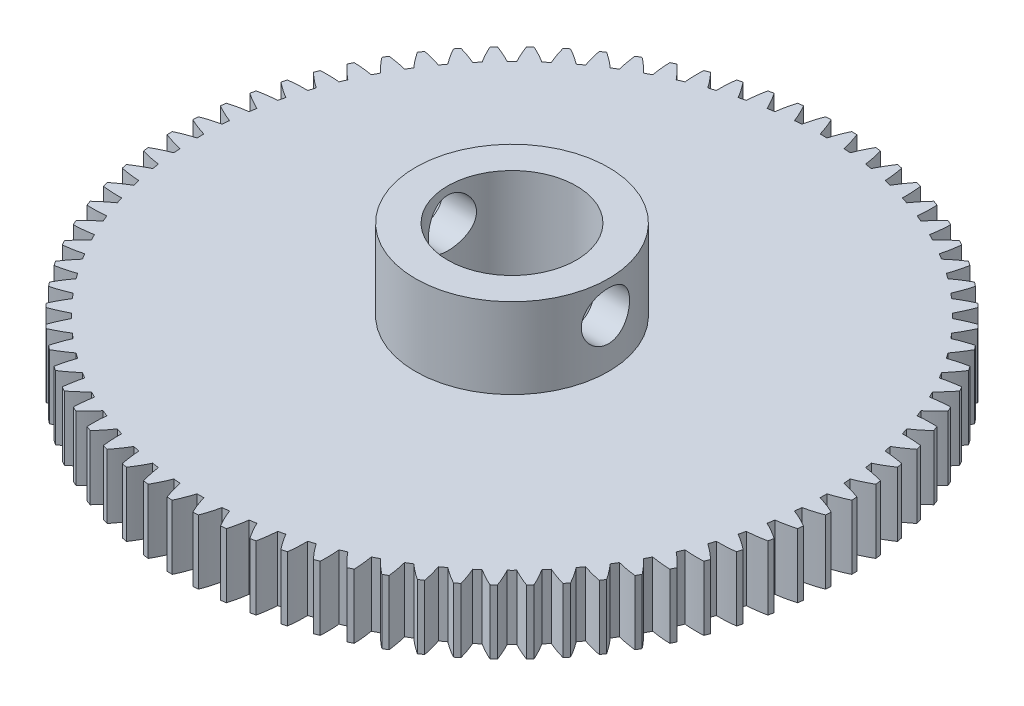
SolidWorks part; units mm, degrees
material "合金鋼"
ref_plane "正面" through (0, 0, 0) normal (0, 0, 1) x (1, 0, 0)
ref_plane "平面" through (0, 0, 0) normal (0, 1, 0) x (1, 0, 0)
ref_plane "右側面" through (0, 0, 0) normal (1, 0, 0) x (0, 0, -1)
sketch "ｽｹｯﾁ1" plane through (0, 0, 0) normal (0, 1, 0) x (1, 0, 0)
  circle B0 centre (0, 0) radius 0.4
  arc B1 (-20.49, 0.64) -> (-19.3729, 0.2101) centre (-17.0665, 7.8705) ccw
  arc B2 (-19.3729, 0.2101) -> (-19.3729, -0.2101) centre (0, 0) ccw
  arc B3 (-19.3729, -0.2101) -> (-20.49, -0.64) centre (-17.0665, -7.8705) ccw
  arc B4 (-20.49, -0.64) -> (-20.4771, -0.9696) centre (0, 0) ccw
  arc B5 (-20.4771, -0.9696) -> (-19.3296, -1.3105) centre (-17.6314, 6.5072) ccw
  arc B6 (-19.3296, -1.3105) -> (-19.2967, -1.7295) centre (0, 0) ccw
  arc B7 (-19.2967, -1.7295) -> (-20.3766, -2.2457) centre (-16.3964, -9.1852) ccw
  arc B8 (-20.3766, -2.2457) -> (-20.3379, -2.5732) centre (0, 0) ccw
  arc B9 (-20.3379, -2.5732) -> (-19.1672, -2.823) centre (-18.0876, 5.1038) ccw
  arc B10 (-19.1672, -2.823) -> (-19.1015, -3.2381) centre (0, 0) ccw
  arc B11 (-19.1015, -3.2381) -> (-20.1376, -3.8375) centre (-15.6252, -10.4433) ccw
  arc B12 (-20.1376, -3.8375) -> (-20.0733, -4.161) centre (0, 0) ccw
  arc B13 (-20.0733, -4.161) -> (-18.8866, -4.3182) centre (-18.4323, 3.6689) ccw
  arc B14 (-18.8866, -4.3182) -> (-18.7885, -4.7268) centre (0, 0) ccw
  arc B15 (-18.7885, -4.7268) -> (-19.7745, -5.4056) centre (-14.7576, -11.6371) ccw
  arc B16 (-19.7745, -5.4056) -> (-19.6849, -5.7231) centre (0, 0) ccw
  arc B17 (-19.6849, -5.7231) -> (-18.4896, -5.7867) centre (-18.6633, 2.2114) ccw
  arc B18 (-18.4896, -5.7867) -> (-18.3598, -6.1864) centre (0, 0) ccw
  arc B19 (-18.3598, -6.1864) -> (-19.2894, -6.9404) centre (-13.7991, -12.7591) ccw
  arc B20 (-19.2894, -6.9404) -> (-19.1752, -7.2499) centre (0, 0) ccw
  arc B21 (-19.1752, -7.2499) -> (-17.9786, -7.2195) centre (-18.7793, 0.7403) ccw
  arc B22 (-17.9786, -7.2195) -> (-17.8178, -7.6078) centre (0, 0) ccw
  arc B23 (-17.8178, -7.6078) -> (-18.6854, -8.4325) centre (-12.7555, -13.8024) ccw
  arc B24 (-18.6854, -8.4325) -> (-18.5473, -8.732) centre (0, 0) ccw
  arc B25 (-18.5473, -8.732) -> (-17.3567, -8.6079) centre (-18.7795, -0.7354) ccw
  arc B26 (-17.3567, -8.6079) -> (-17.1659, -8.9823) centre (0, 0) ccw
  arc B27 (-17.1659, -8.9823) -> (-17.9662, -9.8725) centre (-11.6332, -14.7606) ccw
  arc B28 (-17.9662, -9.8725) -> (-17.805, -10.1603) centre (0, 0) ccw
  arc B29 (-17.805, -10.1603) -> (-16.6279, -9.9431) centre (-18.6639, -2.2065) ccw
  arc B30 (-16.6279, -9.9431) -> (-16.4083, -10.3015) centre (0, 0) ccw
  arc B31 (-16.4083, -10.3015) -> (-17.1362, -11.2517) centre (-10.4393, -15.6279) ccw
  arc B32 (-17.1362, -11.2517) -> (-16.9529, -11.526) centre (0, 0) ccw
  arc B33 (-16.9529, -11.526) -> (-15.7965, -11.2171) centre (-18.4332, -3.6641) ccw
  arc B34 (-15.7965, -11.2171) -> (-15.5495, -11.5571) centre (0, 0) ccw
  arc B35 (-15.5495, -11.5571) -> (-16.2006, -12.5615) centre (-9.1809, -16.3988) ccw
  arc B36 (-16.2006, -12.5615) -> (-15.9964, -12.8205) centre (0, 0) ccw
  arc B37 (-15.9964, -12.8205) -> (-14.8677, -12.4219) centre (-18.0889, -5.0991) ccw
  arc B38 (-14.8677, -12.4219) -> (-14.5948, -12.7414) centre (0, 0) ccw
  arc B39 (-14.5948, -12.7414) -> (-15.1651, -13.7939) centre (-7.866, -17.0685) ccw
  arc B40 (-15.1651, -13.7939) -> (-14.9412, -14.0361) centre (0, 0) ccw
  arc B41 (-14.9412, -14.0361) -> (-13.8473, -13.5501) centre (-17.6331, -6.5026) ccw
  arc B42 (-13.8473, -13.5501) -> (-13.5501, -13.8473) centre (0, 0) ccw
  arc B43 (-13.5501, -13.8473) -> (-14.0361, -14.9412) centre (-6.5026, -17.6331) ccw
  arc B44 (-14.0361, -14.9412) -> (-13.7939, -15.1651) centre (0, 0) ccw
  arc B45 (-13.7939, -15.1651) -> (-12.7414, -14.5948) centre (-17.0685, -7.866) ccw
  arc B46 (-12.7414, -14.5948) -> (-12.4219, -14.8677) centre (0, 0) ccw
  arc B47 (-12.4219, -14.8677) -> (-12.8205, -15.9964) centre (-5.0991, -18.0889) ccw
  arc B48 (-12.8205, -15.9964) -> (-12.5615, -16.2006) centre (0, 0) ccw
  arc B49 (-12.5615, -16.2006) -> (-11.5571, -15.5495) centre (-16.3988, -9.1809) ccw
  arc B50 (-11.5571, -15.5495) -> (-11.2171, -15.7965) centre (0, 0) ccw
  arc B51 (-11.2171, -15.7965) -> (-11.526, -16.9529) centre (-3.6641, -18.4332) ccw
  arc B52 (-11.526, -16.9529) -> (-11.2517, -17.1362) centre (0, 0) ccw
  arc B53 (-11.2517, -17.1362) -> (-10.3015, -16.4083) centre (-15.6279, -10.4393) ccw
  arc B54 (-10.3015, -16.4083) -> (-9.9431, -16.6279) centre (0, 0) ccw
  arc B55 (-9.9431, -16.6279) -> (-10.1603, -17.805) centre (-2.2065, -18.6639) ccw
  arc B56 (-10.1603, -17.805) -> (-9.8725, -17.9662) centre (0, 0) ccw
  arc B57 (-9.8725, -17.9662) -> (-8.9823, -17.1659) centre (-14.7606, -11.6332) ccw
  arc B58 (-8.9823, -17.1659) -> (-8.6079, -17.3567) centre (0, 0) ccw
  arc B59 (-8.6079, -17.3567) -> (-8.732, -18.5473) centre (-0.7354, -18.7795) ccw
  arc B60 (-8.732, -18.5473) -> (-8.4325, -18.6854) centre (0, 0) ccw
  arc B61 (-8.4325, -18.6854) -> (-7.6078, -17.8178) centre (-13.8024, -12.7555) ccw
  arc B62 (-7.6078, -17.8178) -> (-7.2195, -17.9786) centre (0, 0) ccw
  arc B63 (-7.2195, -17.9786) -> (-7.2499, -19.1752) centre (0.7403, -18.7793) ccw
  arc B64 (-7.2499, -19.1752) -> (-6.9404, -19.2894) centre (0, 0) ccw
  arc B65 (-6.9404, -19.2894) -> (-6.1864, -18.3598) centre (-12.7591, -13.7991) ccw
  arc B66 (-6.1864, -18.3598) -> (-5.7867, -18.4896) centre (0, 0) ccw
  arc B67 (-5.7867, -18.4896) -> (-5.7231, -19.6849) centre (2.2114, -18.6633) ccw
  arc B68 (-5.7231, -19.6849) -> (-5.4056, -19.7745) centre (0, 0) ccw
  arc B69 (-5.4056, -19.7745) -> (-4.7268, -18.7885) centre (-11.6371, -14.7576) ccw
  arc B70 (-4.7268, -18.7885) -> (-4.3182, -18.8866) centre (0, 0) ccw
  arc B71 (-4.3182, -18.8866) -> (-4.161, -20.0733) centre (3.6689, -18.4323) ccw
  arc B72 (-4.161, -20.0733) -> (-3.8375, -20.1376) centre (0, 0) ccw
  arc B73 (-3.8375, -20.1376) -> (-3.2381, -19.1015) centre (-10.4433, -15.6252) ccw
  arc B74 (-3.2381, -19.1015) -> (-2.823, -19.1672) centre (0, 0) ccw
  arc B75 (-2.823, -19.1672) -> (-2.5732, -20.3379) centre (5.1038, -18.0876) ccw
  arc B76 (-2.5732, -20.3379) -> (-2.2457, -20.3766) centre (0, 0) ccw
  arc B77 (-2.2457, -20.3766) -> (-1.7295, -19.2967) centre (-9.1852, -16.3964) ccw
  arc B78 (-1.7295, -19.2967) -> (-1.3105, -19.3296) centre (0, 0) ccw
  arc B79 (-1.3105, -19.3296) -> (-0.9696, -20.4771) centre (6.5072, -17.6314) ccw
  arc B80 (-0.9696, -20.4771) -> (-0.64, -20.49) centre (0, 0) ccw
  arc B81 (-0.64, -20.49) -> (-0.2101, -19.3729) centre (-7.8705, -17.0665) ccw
  arc B82 (-0.2101, -19.3729) -> (0.2101, -19.3729) centre (0, 0) ccw
  arc B83 (0.2101, -19.3729) -> (0.64, -20.49) centre (7.8705, -17.0665) ccw
  arc B84 (0.64, -20.49) -> (0.9696, -20.4771) centre (0, 0) ccw
  arc B85 (0.9696, -20.4771) -> (1.3105, -19.3296) centre (-6.5072, -17.6314) ccw
  arc B86 (1.3105, -19.3296) -> (1.7295, -19.2967) centre (0, 0) ccw
  arc B87 (1.7295, -19.2967) -> (2.2457, -20.3766) centre (9.1852, -16.3964) ccw
  arc B88 (2.2457, -20.3766) -> (2.5732, -20.3379) centre (0, 0) ccw
  arc B89 (2.5732, -20.3379) -> (2.823, -19.1672) centre (-5.1038, -18.0876) ccw
  arc B90 (2.823, -19.1672) -> (3.2381, -19.1015) centre (0, 0) ccw
  arc B91 (3.2381, -19.1015) -> (3.8375, -20.1376) centre (10.4433, -15.6252) ccw
  arc B92 (3.8375, -20.1376) -> (4.161, -20.0733) centre (0, 0) ccw
  arc B93 (4.161, -20.0733) -> (4.3182, -18.8866) centre (-3.6689, -18.4323) ccw
  arc B94 (4.3182, -18.8866) -> (4.7268, -18.7885) centre (0, 0) ccw
  arc B95 (4.7268, -18.7885) -> (5.4056, -19.7745) centre (11.6371, -14.7576) ccw
  arc B96 (5.4056, -19.7745) -> (5.7231, -19.6849) centre (0, 0) ccw
  arc B97 (5.7231, -19.6849) -> (5.7867, -18.4896) centre (-2.2114, -18.6633) ccw
  arc B98 (5.7867, -18.4896) -> (6.1864, -18.3598) centre (0, 0) ccw
  arc B99 (6.1864, -18.3598) -> (6.9404, -19.2894) centre (12.7591, -13.7991) ccw
  arc B100 (6.9404, -19.2894) -> (7.2499, -19.1752) centre (0, 0) ccw
  arc B101 (7.2499, -19.1752) -> (7.2195, -17.9786) centre (-0.7403, -18.7793) ccw
  arc B102 (7.2195, -17.9786) -> (7.6078, -17.8178) centre (0, 0) ccw
  arc B103 (7.6078, -17.8178) -> (8.4325, -18.6854) centre (13.8024, -12.7555) ccw
  arc B104 (8.4325, -18.6854) -> (8.732, -18.5473) centre (0, 0) ccw
  arc B105 (8.732, -18.5473) -> (8.6079, -17.3567) centre (0.7354, -18.7795) ccw
  arc B106 (8.6079, -17.3567) -> (8.9823, -17.1659) centre (0, 0) ccw
  arc B107 (8.9823, -17.1659) -> (9.8725, -17.9662) centre (14.7606, -11.6332) ccw
  arc B108 (9.8725, -17.9662) -> (10.1603, -17.805) centre (0, 0) ccw
  arc B109 (10.1603, -17.805) -> (9.9431, -16.6279) centre (2.2065, -18.6639) ccw
  arc B110 (9.9431, -16.6279) -> (10.3015, -16.4083) centre (0, 0) ccw
  arc B111 (10.3015, -16.4083) -> (11.2517, -17.1362) centre (15.6279, -10.4393) ccw
  arc B112 (11.2517, -17.1362) -> (11.526, -16.9529) centre (0, 0) ccw
  arc B113 (11.526, -16.9529) -> (11.2171, -15.7965) centre (3.6641, -18.4332) ccw
  arc B114 (11.2171, -15.7965) -> (11.5571, -15.5495) centre (0, 0) ccw
  arc B115 (11.5571, -15.5495) -> (12.5615, -16.2006) centre (16.3988, -9.1809) ccw
  arc B116 (12.5615, -16.2006) -> (12.8205, -15.9964) centre (0, 0) ccw
  arc B117 (12.8205, -15.9964) -> (12.4219, -14.8677) centre (5.0991, -18.0889) ccw
  arc B118 (12.4219, -14.8677) -> (12.7414, -14.5948) centre (0, 0) ccw
  arc B119 (12.7414, -14.5948) -> (13.7939, -15.1651) centre (17.0685, -7.866) ccw
  arc B120 (13.7939, -15.1651) -> (14.0361, -14.9412) centre (0, 0) ccw
  arc B121 (14.0361, -14.9412) -> (13.5501, -13.8473) centre (6.5026, -17.6331) ccw
  arc B122 (13.5501, -13.8473) -> (13.8473, -13.5501) centre (0, 0) ccw
  arc B123 (13.8473, -13.5501) -> (14.9412, -14.0361) centre (17.6331, -6.5026) ccw
  arc B124 (14.9412, -14.0361) -> (15.1651, -13.7939) centre (0, 0) ccw
  arc B125 (15.1651, -13.7939) -> (14.5948, -12.7414) centre (7.866, -17.0685) ccw
  arc B126 (14.5948, -12.7414) -> (14.8677, -12.4219) centre (0, 0) ccw
  arc B127 (14.8677, -12.4219) -> (15.9964, -12.8205) centre (18.0889, -5.0991) ccw
  arc B128 (15.9964, -12.8205) -> (16.2006, -12.5615) centre (0, 0) ccw
  arc B129 (16.2006, -12.5615) -> (15.5495, -11.5571) centre (9.1809, -16.3988) ccw
  arc B130 (15.5495, -11.5571) -> (15.7965, -11.2171) centre (0, 0) ccw
  arc B131 (15.7965, -11.2171) -> (16.9529, -11.526) centre (18.4332, -3.6641) ccw
  arc B132 (16.9529, -11.526) -> (17.1362, -11.2517) centre (0, 0) ccw
  arc B133 (17.1362, -11.2517) -> (16.4083, -10.3015) centre (10.4393, -15.6279) ccw
  arc B134 (16.4083, -10.3015) -> (16.6279, -9.9431) centre (0, 0) ccw
  arc B135 (16.6279, -9.9431) -> (17.805, -10.1603) centre (18.6639, -2.2065) ccw
  arc B136 (17.805, -10.1603) -> (17.9662, -9.8725) centre (0, 0) ccw
  arc B137 (17.9662, -9.8725) -> (17.1659, -8.9823) centre (11.6332, -14.7606) ccw
  arc B138 (17.1659, -8.9823) -> (17.3567, -8.6079) centre (0, 0) ccw
  arc B139 (17.3567, -8.6079) -> (18.5473, -8.732) centre (18.7795, -0.7354) ccw
  arc B140 (18.5473, -8.732) -> (18.6854, -8.4325) centre (0, 0) ccw
  arc B141 (18.6854, -8.4325) -> (17.8178, -7.6078) centre (12.7555, -13.8024) ccw
  arc B142 (17.8178, -7.6078) -> (17.9786, -7.2195) centre (0, 0) ccw
  arc B143 (17.9786, -7.2195) -> (19.1752, -7.2499) centre (18.7793, 0.7403) ccw
  arc B144 (19.1752, -7.2499) -> (19.2894, -6.9404) centre (0, 0) ccw
  arc B145 (19.2894, -6.9404) -> (18.3598, -6.1864) centre (13.7991, -12.7591) ccw
  arc B146 (18.3598, -6.1864) -> (18.4896, -5.7867) centre (0, 0) ccw
  arc B147 (18.4896, -5.7867) -> (19.6849, -5.7231) centre (18.6633, 2.2114) ccw
  arc B148 (19.6849, -5.7231) -> (19.7745, -5.4056) centre (0, 0) ccw
  arc B149 (19.7745, -5.4056) -> (18.7885, -4.7268) centre (14.7576, -11.6371) ccw
  arc B150 (18.7885, -4.7268) -> (18.8866, -4.3182) centre (0, 0) ccw
  arc B151 (18.8866, -4.3182) -> (20.0733, -4.161) centre (18.4323, 3.6689) ccw
  arc B152 (20.0733, -4.161) -> (20.1376, -3.8375) centre (0, 0) ccw
  arc B153 (20.1376, -3.8375) -> (19.1015, -3.2381) centre (15.6252, -10.4433) ccw
  arc B154 (19.1015, -3.2381) -> (19.1672, -2.823) centre (0, 0) ccw
  arc B155 (19.1672, -2.823) -> (20.3379, -2.5732) centre (18.0876, 5.1038) ccw
  arc B156 (20.3379, -2.5732) -> (20.3766, -2.2457) centre (0, 0) ccw
  arc B157 (20.3766, -2.2457) -> (19.2967, -1.7295) centre (16.3964, -9.1852) ccw
  arc B158 (19.2967, -1.7295) -> (19.3296, -1.3105) centre (0, 0) ccw
  arc B159 (19.3296, -1.3105) -> (20.4771, -0.9696) centre (17.6314, 6.5072) ccw
  arc B160 (20.4771, -0.9696) -> (20.49, -0.64) centre (0, 0) ccw
  arc B161 (20.49, -0.64) -> (19.3729, -0.2101) centre (17.0665, -7.8705) ccw
  arc B162 (19.3729, -0.2101) -> (19.3729, 0.2101) centre (0, 0) ccw
  arc B163 (19.3729, 0.2101) -> (20.49, 0.64) centre (17.0665, 7.8705) ccw
  arc B164 (20.49, 0.64) -> (20.4771, 0.9696) centre (0, 0) ccw
  arc B165 (20.4771, 0.9696) -> (19.3296, 1.3105) centre (17.6314, -6.5072) ccw
  arc B166 (19.3296, 1.3105) -> (19.2967, 1.7295) centre (0, 0) ccw
  arc B167 (19.2967, 1.7295) -> (20.3766, 2.2457) centre (16.3964, 9.1852) ccw
  arc B168 (20.3766, 2.2457) -> (20.3379, 2.5732) centre (0, 0) ccw
  arc B169 (20.3379, 2.5732) -> (19.1672, 2.823) centre (18.0876, -5.1038) ccw
  arc B170 (19.1672, 2.823) -> (19.1015, 3.2381) centre (0, 0) ccw
  arc B171 (19.1015, 3.2381) -> (20.1376, 3.8375) centre (15.6252, 10.4433) ccw
  arc B172 (20.1376, 3.8375) -> (20.0733, 4.161) centre (0, 0) ccw
  arc B173 (20.0733, 4.161) -> (18.8866, 4.3182) centre (18.4323, -3.6689) ccw
  arc B174 (18.8866, 4.3182) -> (18.7885, 4.7268) centre (0, 0) ccw
  arc B175 (18.7885, 4.7268) -> (19.7745, 5.4056) centre (14.7576, 11.6371) ccw
  arc B176 (19.7745, 5.4056) -> (19.6849, 5.7231) centre (0, 0) ccw
  arc B177 (19.6849, 5.7231) -> (18.4896, 5.7867) centre (18.6633, -2.2114) ccw
  arc B178 (18.4896, 5.7867) -> (18.3598, 6.1864) centre (0, 0) ccw
  arc B179 (18.3598, 6.1864) -> (19.2894, 6.9404) centre (13.7991, 12.7591) ccw
  arc B180 (19.2894, 6.9404) -> (19.1752, 7.2499) centre (0, 0) ccw
  arc B181 (19.1752, 7.2499) -> (17.9786, 7.2195) centre (18.7793, -0.7403) ccw
  arc B182 (17.9786, 7.2195) -> (17.8178, 7.6078) centre (0, 0) ccw
  arc B183 (17.8178, 7.6078) -> (18.6854, 8.4325) centre (12.7555, 13.8024) ccw
  arc B184 (18.6854, 8.4325) -> (18.5473, 8.732) centre (0, 0) ccw
  arc B185 (18.5473, 8.732) -> (17.3567, 8.6079) centre (18.7795, 0.7354) ccw
  arc B186 (17.3567, 8.6079) -> (17.1659, 8.9823) centre (0, 0) ccw
  arc B187 (17.1659, 8.9823) -> (17.9662, 9.8725) centre (11.6332, 14.7606) ccw
  arc B188 (17.9662, 9.8725) -> (17.805, 10.1603) centre (0, 0) ccw
  arc B189 (17.805, 10.1603) -> (16.6279, 9.9431) centre (18.6639, 2.2065) ccw
  arc B190 (16.6279, 9.9431) -> (16.4083, 10.3015) centre (0, 0) ccw
  arc B191 (16.4083, 10.3015) -> (17.1362, 11.2517) centre (10.4393, 15.6279) ccw
  arc B192 (17.1362, 11.2517) -> (16.9529, 11.526) centre (0, 0) ccw
  arc B193 (16.9529, 11.526) -> (15.7965, 11.2171) centre (18.4332, 3.6641) ccw
  arc B194 (15.7965, 11.2171) -> (15.5495, 11.5571) centre (0, 0) ccw
  arc B195 (15.5495, 11.5571) -> (16.2006, 12.5615) centre (9.1809, 16.3988) ccw
  arc B196 (16.2006, 12.5615) -> (15.9964, 12.8205) centre (0, 0) ccw
  arc B197 (15.9964, 12.8205) -> (14.8677, 12.4219) centre (18.0889, 5.0991) ccw
  arc B198 (14.8677, 12.4219) -> (14.5948, 12.7414) centre (0, 0) ccw
  arc B199 (14.5948, 12.7414) -> (15.1651, 13.7939) centre (7.866, 17.0685) ccw
  arc B200 (15.1651, 13.7939) -> (14.9412, 14.0361) centre (0, 0) ccw
  arc B201 (14.9412, 14.0361) -> (13.8473, 13.5501) centre (17.6331, 6.5026) ccw
  arc B202 (13.8473, 13.5501) -> (13.5501, 13.8473) centre (0, 0) ccw
  arc B203 (13.5501, 13.8473) -> (14.0361, 14.9412) centre (6.5026, 17.6331) ccw
  arc B204 (14.0361, 14.9412) -> (13.7939, 15.1651) centre (0, 0) ccw
  arc B205 (13.7939, 15.1651) -> (12.7414, 14.5948) centre (17.0685, 7.866) ccw
  arc B206 (12.7414, 14.5948) -> (12.4219, 14.8677) centre (0, 0) ccw
  arc B207 (12.4219, 14.8677) -> (12.8205, 15.9964) centre (5.0991, 18.0889) ccw
  arc B208 (12.8205, 15.9964) -> (12.5615, 16.2006) centre (0, 0) ccw
  arc B209 (12.5615, 16.2006) -> (11.5571, 15.5495) centre (16.3988, 9.1809) ccw
  arc B210 (11.5571, 15.5495) -> (11.2171, 15.7965) centre (0, 0) ccw
  arc B211 (11.2171, 15.7965) -> (11.526, 16.9529) centre (3.6641, 18.4332) ccw
  arc B212 (11.526, 16.9529) -> (11.2517, 17.1362) centre (0, 0) ccw
  arc B213 (11.2517, 17.1362) -> (10.3015, 16.4083) centre (15.6279, 10.4393) ccw
  arc B214 (10.3015, 16.4083) -> (9.9431, 16.6279) centre (0, 0) ccw
  arc B215 (9.9431, 16.6279) -> (10.1603, 17.805) centre (2.2065, 18.6639) ccw
  arc B216 (10.1603, 17.805) -> (9.8725, 17.9662) centre (0, 0) ccw
  arc B217 (9.8725, 17.9662) -> (8.9823, 17.1659) centre (14.7606, 11.6332) ccw
  arc B218 (8.9823, 17.1659) -> (8.6079, 17.3567) centre (0, 0) ccw
  arc B219 (8.6079, 17.3567) -> (8.732, 18.5473) centre (0.7354, 18.7795) ccw
  arc B220 (8.732, 18.5473) -> (8.4325, 18.6854) centre (0, 0) ccw
  arc B221 (8.4325, 18.6854) -> (7.6078, 17.8178) centre (13.8024, 12.7555) ccw
  arc B222 (7.6078, 17.8178) -> (7.2195, 17.9786) centre (0, 0) ccw
  arc B223 (7.2195, 17.9786) -> (7.2499, 19.1752) centre (-0.7403, 18.7793) ccw
  arc B224 (7.2499, 19.1752) -> (6.9404, 19.2894) centre (0, 0) ccw
  arc B225 (6.9404, 19.2894) -> (6.1864, 18.3598) centre (12.7591, 13.7991) ccw
  arc B226 (6.1864, 18.3598) -> (5.7867, 18.4896) centre (0, 0) ccw
  arc B227 (5.7867, 18.4896) -> (5.7231, 19.6849) centre (-2.2114, 18.6633) ccw
  arc B228 (5.7231, 19.6849) -> (5.4056, 19.7745) centre (0, 0) ccw
  arc B229 (5.4056, 19.7745) -> (4.7268, 18.7885) centre (11.6371, 14.7576) ccw
  arc B230 (4.7268, 18.7885) -> (4.3182, 18.8866) centre (0, 0) ccw
  arc B231 (4.3182, 18.8866) -> (4.161, 20.0733) centre (-3.6689, 18.4323) ccw
  arc B232 (4.161, 20.0733) -> (3.8375, 20.1376) centre (0, 0) ccw
  arc B233 (3.8375, 20.1376) -> (3.2381, 19.1015) centre (10.4433, 15.6252) ccw
  arc B234 (3.2381, 19.1015) -> (2.823, 19.1672) centre (0, 0) ccw
  arc B235 (2.823, 19.1672) -> (2.5732, 20.3379) centre (-5.1038, 18.0876) ccw
  arc B236 (2.5732, 20.3379) -> (2.2457, 20.3766) centre (0, 0) ccw
  arc B237 (2.2457, 20.3766) -> (1.7295, 19.2967) centre (9.1852, 16.3964) ccw
  arc B238 (1.7295, 19.2967) -> (1.3105, 19.3296) centre (0, 0) ccw
  arc B239 (1.3105, 19.3296) -> (0.9696, 20.4771) centre (-6.5072, 17.6314) ccw
  arc B240 (0.9696, 20.4771) -> (0.64, 20.49) centre (0, 0) ccw
  arc B241 (0.64, 20.49) -> (0.2101, 19.3729) centre (7.8705, 17.0665) ccw
  arc B242 (0.2101, 19.3729) -> (-0.2101, 19.3729) centre (0, 0) ccw
  arc B243 (-0.2101, 19.3729) -> (-0.64, 20.49) centre (-7.8705, 17.0665) ccw
  arc B244 (-0.64, 20.49) -> (-0.9696, 20.4771) centre (0, 0) ccw
  arc B245 (-0.9696, 20.4771) -> (-1.3105, 19.3296) centre (6.5072, 17.6314) ccw
  arc B246 (-1.3105, 19.3296) -> (-1.7295, 19.2967) centre (0, 0) ccw
  arc B247 (-1.7295, 19.2967) -> (-2.2457, 20.3766) centre (-9.1852, 16.3964) ccw
  arc B248 (-2.2457, 20.3766) -> (-2.5732, 20.3379) centre (0, 0) ccw
  arc B249 (-2.5732, 20.3379) -> (-2.823, 19.1672) centre (5.1038, 18.0876) ccw
  arc B250 (-2.823, 19.1672) -> (-3.2381, 19.1015) centre (0, 0) ccw
  arc B251 (-3.2381, 19.1015) -> (-3.8375, 20.1376) centre (-10.4433, 15.6252) ccw
  arc B252 (-3.8375, 20.1376) -> (-4.161, 20.0733) centre (0, 0) ccw
  arc B253 (-4.161, 20.0733) -> (-4.3182, 18.8866) centre (3.6689, 18.4323) ccw
  arc B254 (-4.3182, 18.8866) -> (-4.7268, 18.7885) centre (0, 0) ccw
  arc B255 (-4.7268, 18.7885) -> (-5.4056, 19.7745) centre (-11.6371, 14.7576) ccw
  arc B256 (-5.4056, 19.7745) -> (-5.7231, 19.6849) centre (0, 0) ccw
  arc B257 (-5.7231, 19.6849) -> (-5.7867, 18.4896) centre (2.2114, 18.6633) ccw
  arc B258 (-5.7867, 18.4896) -> (-6.1864, 18.3598) centre (0, 0) ccw
  arc B259 (-6.1864, 18.3598) -> (-6.9404, 19.2894) centre (-12.7591, 13.7991) ccw
  arc B260 (-6.9404, 19.2894) -> (-7.2499, 19.1752) centre (0, 0) ccw
  arc B261 (-7.2499, 19.1752) -> (-7.2195, 17.9786) centre (0.7403, 18.7793) ccw
  arc B262 (-7.2195, 17.9786) -> (-7.6078, 17.8178) centre (0, 0) ccw
  arc B263 (-7.6078, 17.8178) -> (-8.4325, 18.6854) centre (-13.8024, 12.7555) ccw
  arc B264 (-8.4325, 18.6854) -> (-8.732, 18.5473) centre (0, 0) ccw
  arc B265 (-8.732, 18.5473) -> (-8.6079, 17.3567) centre (-0.7354, 18.7795) ccw
  arc B266 (-8.6079, 17.3567) -> (-8.9823, 17.1659) centre (0, 0) ccw
  arc B267 (-8.9823, 17.1659) -> (-9.8725, 17.9662) centre (-14.7606, 11.6332) ccw
  arc B268 (-9.8725, 17.9662) -> (-10.1603, 17.805) centre (0, 0) ccw
  arc B269 (-10.1603, 17.805) -> (-9.9431, 16.6279) centre (-2.2065, 18.6639) ccw
  arc B270 (-9.9431, 16.6279) -> (-10.3015, 16.4083) centre (0, 0) ccw
  arc B271 (-10.3015, 16.4083) -> (-11.2517, 17.1362) centre (-15.6279, 10.4393) ccw
  arc B272 (-11.2517, 17.1362) -> (-11.526, 16.9529) centre (0, 0) ccw
  arc B273 (-11.526, 16.9529) -> (-11.2171, 15.7965) centre (-3.6641, 18.4332) ccw
  arc B274 (-11.2171, 15.7965) -> (-11.5571, 15.5495) centre (0, 0) ccw
  arc B275 (-11.5571, 15.5495) -> (-12.5615, 16.2006) centre (-16.3988, 9.1809) ccw
  arc B276 (-12.5615, 16.2006) -> (-12.8205, 15.9964) centre (0, 0) ccw
  arc B277 (-12.8205, 15.9964) -> (-12.4219, 14.8677) centre (-5.0991, 18.0889) ccw
  arc B278 (-12.4219, 14.8677) -> (-12.7414, 14.5948) centre (0, 0) ccw
  arc B279 (-12.7414, 14.5948) -> (-13.7939, 15.1651) centre (-17.0685, 7.866) ccw
  arc B280 (-13.7939, 15.1651) -> (-14.0361, 14.9412) centre (0, 0) ccw
  arc B281 (-14.0361, 14.9412) -> (-13.5501, 13.8473) centre (-6.5026, 17.6331) ccw
  arc B282 (-13.5501, 13.8473) -> (-13.8473, 13.5501) centre (0, 0) ccw
  arc B283 (-13.8473, 13.5501) -> (-14.9412, 14.0361) centre (-17.6331, 6.5026) ccw
  arc B284 (-14.9412, 14.0361) -> (-15.1651, 13.7939) centre (0, 0) ccw
  arc B285 (-15.1651, 13.7939) -> (-14.5948, 12.7414) centre (-7.866, 17.0685) ccw
  arc B286 (-14.5948, 12.7414) -> (-14.8677, 12.4219) centre (0, 0) ccw
  arc B287 (-14.8677, 12.4219) -> (-15.9964, 12.8205) centre (-18.0889, 5.0991) ccw
  arc B288 (-15.9964, 12.8205) -> (-16.2006, 12.5615) centre (0, 0) ccw
  arc B289 (-16.2006, 12.5615) -> (-15.5495, 11.5571) centre (-9.1809, 16.3988) ccw
  arc B290 (-15.5495, 11.5571) -> (-15.7965, 11.2171) centre (0, 0) ccw
  arc B291 (-15.7965, 11.2171) -> (-16.9529, 11.526) centre (-18.4332, 3.6641) ccw
  arc B292 (-16.9529, 11.526) -> (-17.1362, 11.2517) centre (0, 0) ccw
  arc B293 (-17.1362, 11.2517) -> (-16.4083, 10.3015) centre (-10.4393, 15.6279) ccw
  arc B294 (-16.4083, 10.3015) -> (-16.6279, 9.9431) centre (0, 0) ccw
  arc B295 (-16.6279, 9.9431) -> (-17.805, 10.1603) centre (-18.6639, 2.2065) ccw
  arc B296 (-17.805, 10.1603) -> (-17.9662, 9.8725) centre (0, 0) ccw
  arc B297 (-17.9662, 9.8725) -> (-17.1659, 8.9823) centre (-11.6332, 14.7606) ccw
  arc B298 (-17.1659, 8.9823) -> (-17.3567, 8.6079) centre (0, 0) ccw
  arc B299 (-17.3567, 8.6079) -> (-18.5473, 8.732) centre (-18.7795, 0.7354) ccw
  arc B300 (-18.5473, 8.732) -> (-18.6854, 8.4325) centre (0, 0) ccw
  arc B301 (-18.6854, 8.4325) -> (-17.8178, 7.6078) centre (-12.7555, 13.8024) ccw
  arc B302 (-17.8178, 7.6078) -> (-17.9786, 7.2195) centre (0, 0) ccw
  arc B303 (-17.9786, 7.2195) -> (-19.1752, 7.2499) centre (-18.7793, -0.7403) ccw
  arc B304 (-19.1752, 7.2499) -> (-19.2894, 6.9404) centre (0, 0) ccw
  arc B305 (-19.2894, 6.9404) -> (-18.3598, 6.1864) centre (-13.7991, 12.7591) ccw
  arc B306 (-18.3598, 6.1864) -> (-18.4896, 5.7867) centre (0, 0) ccw
  arc B307 (-18.4896, 5.7867) -> (-19.6849, 5.7231) centre (-18.6633, -2.2114) ccw
  arc B308 (-19.6849, 5.7231) -> (-19.7745, 5.4056) centre (0, 0) ccw
  arc B309 (-19.7745, 5.4056) -> (-18.7885, 4.7268) centre (-14.7576, 11.6371) ccw
  arc B310 (-18.7885, 4.7268) -> (-18.8866, 4.3182) centre (0, 0) ccw
  arc B311 (-18.8866, 4.3182) -> (-20.0733, 4.161) centre (-18.4323, -3.6689) ccw
  arc B312 (-20.0733, 4.161) -> (-20.1376, 3.8375) centre (0, 0) ccw
  arc B313 (-20.1376, 3.8375) -> (-19.1015, 3.2381) centre (-15.6252, 10.4433) ccw
  arc B314 (-19.1015, 3.2381) -> (-19.1672, 2.823) centre (0, 0) ccw
  arc B315 (-19.1672, 2.823) -> (-20.3379, 2.5732) centre (-18.0876, -5.1038) ccw
  arc B316 (-20.3379, 2.5732) -> (-20.3766, 2.2457) centre (0, 0) ccw
  arc B317 (-20.3766, 2.2457) -> (-19.2967, 1.7295) centre (-16.3964, 9.1852) ccw
  arc B318 (-19.2967, 1.7295) -> (-19.3296, 1.3105) centre (0, 0) ccw
  arc B319 (-19.3296, 1.3105) -> (-20.4771, 0.9696) centre (-17.6314, -6.5072) ccw
  arc B320 (-20.4771, 0.9696) -> (-20.49, 0.64) centre (0, 0) ccw
sketch_block_instance "JIS - Spur gear 0.5M 80T 20PA 3FW ---S80A75H50L0.8N-1"
sketch_block "JIS - Spur gear 0.5M 80T 20PA 3FW ---S80A75H50L0.8N"
extrude "ﾎﾞｽ - 押し出し1" add sketch "ｽｹｯﾁ1" along normal blind 4
sketch "ｽｹｯﾁ2" plane through (0, 4, 0) normal (0, 1, 0) x (1, 0, 0)
  circle A0 centre (0, 0) radius 6
  dimension "D1" = 12
extrude "ﾎﾞｽ - 押し出し2" add sketch "ｽｹｯﾁ2" along normal blind 5
sketch "ｽｹｯﾁ3" plane through (0, 9, 0) normal (0, 1, 0) x (1, 0, 0)
  circle A0 centre (0, 0) radius 4
  dimension "D1" = 8
extrude "ｶｯﾄ - 押し出し1" cut sketch "ｽｹｯﾁ3" against normal through all
sketch "ｽｹｯﾁ5" plane through (0, 0, 0) normal (1, 0, 0) x (0, 0, -1)
  line L1 (6, 9) -> (-6, 9) construction
  line L3 (0, 9) -> (0, 7) construction
  circle A0 centre (0, 7) radius 1.5
  dimension "D1" = 3
  dimension "D2" = 2
extrude "ｶｯﾄ - 押し出し3" cut sketch "ｽｹｯﾁ5" against normal through all both and the other way through all
